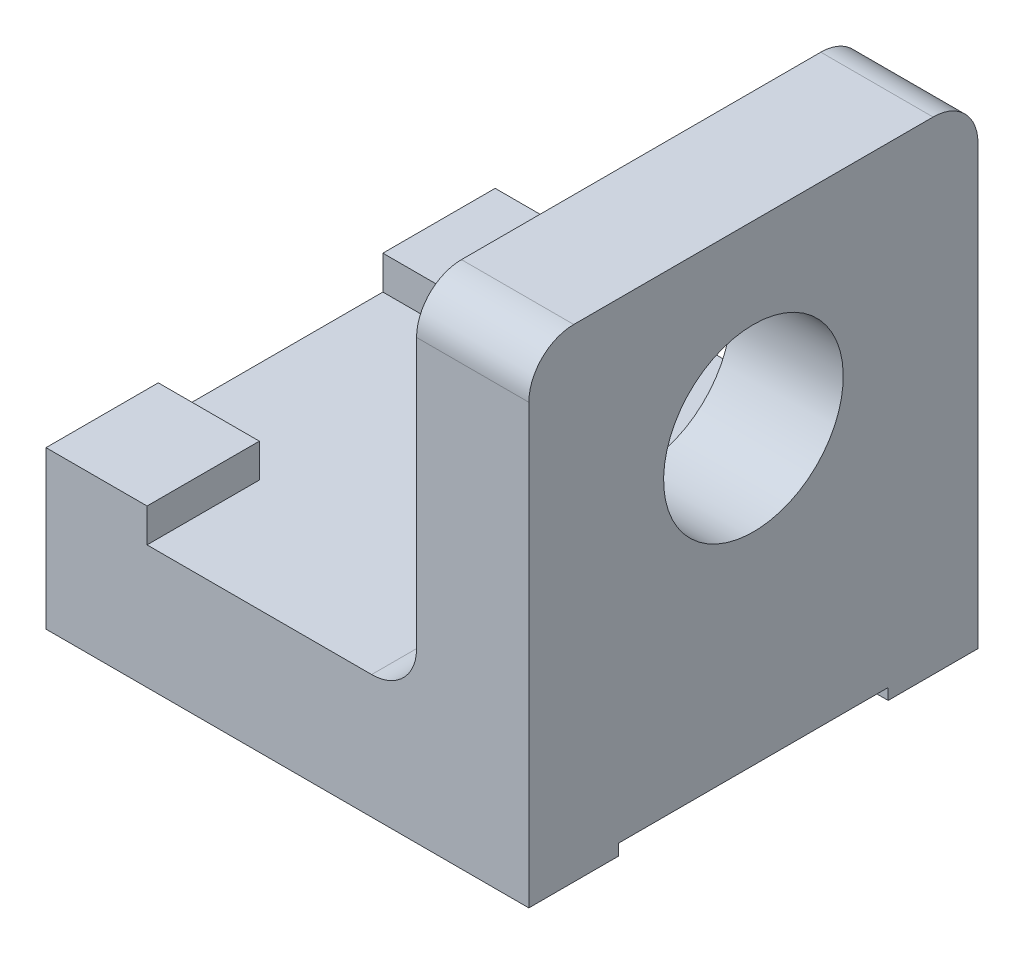
SolidWorks part; units mm, degrees
ref_plane "Front Plane" through (0, 0, 0) normal (0, 0, 1) x (1, 0, 0)
ref_plane "Top Plane" through (0, 0, 0) normal (0, 1, 0) x (1, 0, 0)
ref_plane "Right Plane" through (0, 0, 0) normal (1, 0, 0) x (0, 0, -1)
sketch "Sketch1" plane through (0, 0, 0) normal (0, 0, 1) x (1, 0, 0)
  line L0 (196.2978, 68.2625) -> (196.2978, -68.2625)
  line L1 (196.2978, -68.2625) -> (59.7728, -68.2625)
  line L2 (196.2978, 68.2625) -> (164.5478, 68.2625)
  line L3 (59.7728, -68.2625) -> (59.7728, -23.8125)
  line L4 (59.7728, -23.8125) -> (88.3478, -23.8125)
  line L5 (88.3478, -23.8125) -> (88.3478, -33.3375)
  line L6 (88.3478, -33.3375) -> (164.5478, -33.3375)
  line L7 (164.5478, -33.3375) -> (164.5478, 68.2625)
  dimension "D1" = 136.525
  dimension "D2" = 68.2625
  dimension "D3" = 136.525
  dimension "D4" = 44.45
  dimension "D5" = 31.75
  dimension "D6" = 9.525
  dimension "D7" = 76.2
extrude "Boss-Extrude1" add sketch "Sketch1" along normal blind 127
sketch "Sketch2" plane through (196.2978, 0, 0) normal (1, 0, 0) x (0, 0, -1)
  line L0 (-127, 68.2625) -> (0, 68.2625) construction
  line L1 (0, -68.2625) -> (0, 68.2625) construction
  circle A0 centre (-63.5, 17.4625) radius 25.4
  dimension "D1" = 50.8
  dimension "D2" = 50.8
  dimension "D3" = 63.5
extrude "Cut-Extrude1" cut sketch "Sketch2" against normal blind 127
sketch "Sketch3" plane through (59.7728, 0, 0) normal (-1, 0, 0) x (0, 0, 1)
  line L0 (127, -68.2625) -> (0, -68.2625) construction
  line L1 (25.4, -68.2625) -> (101.6, -68.2625)
  line L2 (25.4, -68.2625) -> (25.4, -65.0875)
  line L3 (25.4, -65.0875) -> (101.6, -65.0875)
  line L4 (101.6, -68.2625) -> (101.6, -65.0875)
  line L5 (0, -23.8125) -> (0, -68.2625) construction
  dimension "D1" = 76.2
  dimension "D2" = 3.175
  dimension "D3" = 25.4
extrude "Cut-Extrude2" cut sketch "Sketch3" against normal through all
sketch "Sketch4" plane through (59.7728, 0, 0) normal (-1, 0, 0) x (0, 0, 1)
  line L0 (127, -23.8125) -> (0, -23.8125) construction
  line L1 (31.75, -23.8125) -> (95.25, -23.8125)
  line L2 (31.75, -23.8125) -> (31.75, -33.3375)
  line L3 (31.75, -33.3375) -> (95.25, -33.3375)
  line L4 (95.25, -23.8125) -> (95.25, -33.3375)
  line L5 (0, -23.8125) -> (0, -68.2625) construction
  dimension "D1" = 9.525
  dimension "D2" = 63.5
  dimension "D3" = 31.75
extrude "Cut-Extrude4" cut sketch "Sketch4" against normal blind 50.038
fillet "Fillet1" radius 12.7 3 edges at (164.5478, -33.3375, 63.5) (180.4228, 68.2625, 127) (180.4228, 68.2625, 0)
